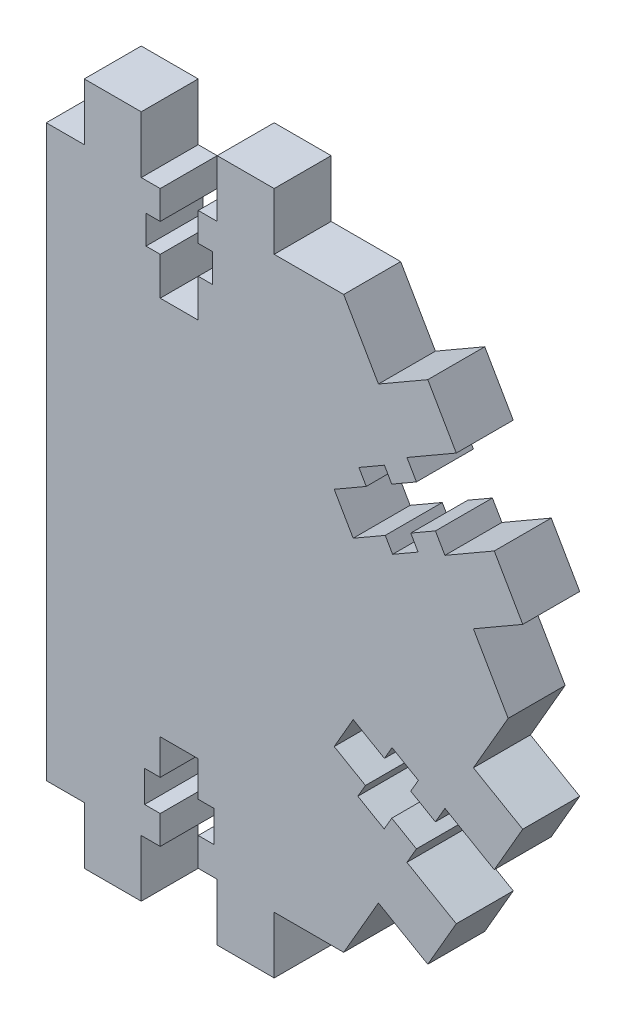
SolidWorks part; units mm, degrees
ref_plane "Plan de face" through (0, 0, 0) normal (0, 0, 1) x (1, 0, 0)
ref_plane "Plan de dessus" through (0, 0, 0) normal (0, 1, 0) x (1, 0, 0)
ref_plane "Plan de droite" through (0, 0, 0) normal (1, 0, 0) x (0, 0, -1)
sketch "Esquisse1" plane through (0, 0, 0) normal (0, 0, 1) x (1, 0, 0)
  line L0 (0, 0) -> (0, 30) construction
  line L1 (0, 0) -> (25.9808, 15) construction
  line L2 (0, 0) -> (25.9808, -15) construction
  line L3 (0, 0) -> (0, -30) construction
  line L4 (0, 0) -> (-25.9808, -15) construction
  line L5 (0, 0) -> (-25.9808, 15) construction
  line L6 (10, 30) -> (17.3205, 30)
  line L7 (17.3205, 30) -> (20.9808, 23.6603)
  line L8 (30.9808, 6.3397) -> (34.641, 0)
  line L9 (34.641, 0) -> (30.9808, -6.3397)
  line L10 (20.9808, -23.6603) -> (17.3205, -30)
  line L11 (17.3205, -30) -> (10, -30)
  line L12 (-10, -30) -> (-14, -30)
  line L13 (-14, -30) -> (-14, 30)
  line L14 (-14, 30) -> (-10, 30)
  line L15 (25.9808, 15) -> (17.3205, 10) construction
  line L16 (26.9808, 13.2679) -> (27.9808, 11.5359)
  line L17 (33.1769, 14.5359) -> (36.1769, 9.3397)
  line L18 (36.1769, 9.3397) -> (30.9808, 6.3397)
  line L19 (33.1769, 14.5359) -> (27.9808, 11.5359)
  line L20 (24.9808, 16.7321) -> (23.9808, 18.4641)
  line L21 (23.9808, 18.4641) -> (29.1769, 21.4641)
  line L22 (29.1769, 21.4641) -> (26.1769, 26.6603)
  line L23 (26.1769, 26.6603) -> (20.9808, 23.6603)
  line L24 (26.9808, 13.2679) -> (24.9808, 16.7321) construction
  line L25 (24.9808, 16.7321) -> (22.3827, 15.2321)
  line L26 (19.698, 13.6821) -> (18.923, 15.0244)
  line L27 (25.1577, 10.4256) -> (22.473, 8.8756)
  line L28 (21.6077, 16.5744) -> (22.3827, 15.2321)
  line L29 (19.698, 13.6821) -> (16.3205, 11.7321)
  line L30 (16.3205, 11.7321) -> (18.3205, 8.2679)
  line L31 (18.3205, 8.2679) -> (21.698, 10.2179)
  line L32 (24.3827, 11.7679) -> (25.1577, 10.4256)
  line L33 (18.923, 15.0244) -> (21.6077, 16.5744)
  line L34 (22.473, 8.8756) -> (21.698, 10.2179)
  line L35 (24.3827, 11.7679) -> (26.9808, 13.2679)
  line L36 (17.3205, 10) -> (25.9808, 15) construction
  line L37 (25.9808, -15) -> (17.1293, -9.8896) construction
  line L38 (24.9808, -16.7321) -> (23.9808, -18.4641)
  line L39 (29.1769, -21.4641) -> (26.1769, -26.6603)
  line L40 (26.1769, -26.6603) -> (20.9808, -23.6603)
  line L41 (29.1769, -21.4641) -> (23.9808, -18.4641)
  line L42 (26.9808, -13.2679) -> (27.9808, -11.5359)
  line L43 (27.9808, -11.5359) -> (33.1769, -14.5359)
  line L44 (33.1769, -14.5359) -> (36.1769, -9.3397)
  line L45 (36.1769, -9.3397) -> (30.9808, -6.3397)
  line L46 (24.9808, -16.7321) -> (26.9808, -13.2679) construction
  line L47 (26.9808, -13.2679) -> (24.3827, -11.7679)
  line L48 (21.6114, -10.1679) -> (22.4114, -8.7823)
  line L49 (21.5827, -16.6177) -> (18.8114, -15.0177)
  line L50 (25.1827, -10.3823) -> (24.3827, -11.7679)
  line L51 (21.6114, -10.1679) -> (18.3205, -8.2679)
  line L52 (18.3205, -8.2679) -> (16.3205, -11.7321)
  line L53 (16.3205, -11.7321) -> (19.6114, -13.6321)
  line L54 (22.3827, -15.2321) -> (21.5827, -16.6177)
  line L55 (22.4114, -8.7823) -> (25.1827, -10.3823)
  line L56 (18.8114, -15.0177) -> (19.6114, -13.6321)
  line L57 (22.3827, -15.2321) -> (24.9808, -16.7321)
  line L58 (17.3205, -10) -> (25.9808, -15) construction
  line L59 (0, 30) -> (0, 19.7792) construction
  line L60 (2, 30) -> (4, 30)
  line L61 (4, 36) -> (10, 36)
  line L62 (10, 36) -> (10, 30)
  line L63 (4, 36) -> (4, 30)
  line L64 (-2, 30) -> (-4, 30)
  line L65 (-4, 30) -> (-4, 36)
  line L66 (-4, 36) -> (-10, 36)
  line L67 (-10, 36) -> (-10, 30)
  line L68 (2, 30) -> (-2, 30) construction
  line L69 (-2, 30) -> (-2, 27)
  line L70 (-2, 24) -> (-3.5, 24)
  line L71 (3.5, 27) -> (3.5, 24)
  line L72 (-3.5, 27) -> (-2, 27)
  line L73 (-2, 24) -> (-2, 20)
  line L74 (-2, 20) -> (2, 20)
  line L75 (2, 20) -> (2, 24)
  line L76 (2, 27) -> (3.5, 27)
  line L77 (-3.5, 24) -> (-3.5, 27)
  line L78 (3.5, 24) -> (2, 24)
  line L79 (2, 27) -> (2, 30)
  line L80 (0, 20) -> (0, 30) construction
  line L81 (0, -30) -> (0, -19.7792) construction
  line L82 (-2, -30) -> (-4, -30)
  line L83 (-4, -36) -> (-10, -36)
  line L84 (-10, -36) -> (-10, -30)
  line L85 (-4, -36) -> (-4, -30)
  line L86 (2, -30) -> (4, -30)
  line L87 (4, -30) -> (4, -36)
  line L88 (4, -36) -> (10, -36)
  line L89 (10, -36) -> (10, -30)
  line L90 (-2, -30) -> (2, -30) construction
  line L91 (2, -30) -> (2, -27)
  line L92 (2, -23.7) -> (3.65, -23.7)
  line L93 (-3.65, -27) -> (-3.65, -23.7)
  line L94 (3.65, -27) -> (2, -27)
  line L95 (2, -23.7) -> (2, -20)
  line L96 (2, -20) -> (-2, -20)
  line L97 (-2, -20) -> (-2, -23.7)
  line L98 (-2, -27) -> (-3.65, -27)
  line L99 (3.65, -23.7) -> (3.65, -27)
  line L100 (-3.65, -23.7) -> (-2, -23.7)
  line L101 (-2, -27) -> (-2, -30)
  line L102 (0, -20) -> (0, -30) construction
  point P9 (0, 0)
  point P21 (0, -30)
  point P23 (10, -30)
  point P24 (0, -19.7792)
  point P25 (0, 0)
  point P28 (27.9808, 13.4803)
  point P33 (17.4953, 9.3803)
  point P48 (27.3936, -13.2679)
  point P51 (24.9197, -17.1299)
  point P56 (27.8892, 11.494)
  point P79 (2.1771, -30)
  point P97 (-14.3881, -30)
  point P100 (10, 34.8901)
  point P102 (2, 30.3187)
  point P119 (24.9808, 16.9908)
  point P120 (17.1293, 10.3745)
  point P121 (28.2699, 13.7706)
  point P122 (30.9808, 6.3397)
  point P123 (34.4542, 0.3236)
  point P124 (-1.8323, -30)
  point P125 (10, 30.7956)
  point P126 (0, 0)
  dimension "D2" = 30
  dimension "D3" = 6
  dimension "D4" = 6
  dimension "D5" = 20
  dimension "D6" = 7.1
  dimension "D7" = 4
  dimension "D8" = 3.1
  dimension "D9" = 3
  dimension "D10" = 10
  dimension "D11" = 6
  dimension "D12" = 6
  dimension "D13" = 20
  dimension "D14" = 7.2
  dimension "D15" = 4
  dimension "D16" = 3.2
  dimension "D17" = 3
  dimension "D18" = 10
  dimension "D19" = 6
  dimension "D20" = 6
  dimension "D21" = 20
  dimension "D22" = 7
  dimension "D23" = 4
  dimension "D24" = 3
  dimension "D25" = 3
  dimension "D26" = 10
  dimension "D27" = 6
  dimension "D28" = 6
  dimension "D29" = 20
  dimension "D30" = 7.3
  dimension "D31" = 4
  dimension "D32" = 3.3
  dimension "D33" = 3
  dimension "D34" = 10
  dimension "D35" = 14
  dimension "D1" = 6
extrude "Boss.-Extru.1" add sketch "Esquisse1" along normal blind 6
